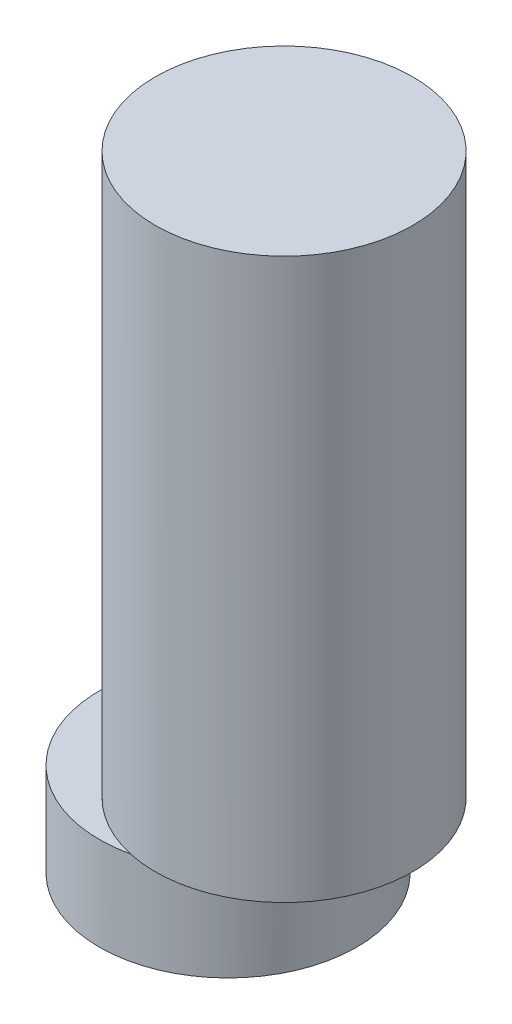
SolidWorks part; units mm, degrees
ref_plane "Front Plane" through (0, 0, 0) normal (0, 0, 1) x (1, 0, 0)
ref_plane "Top Plane" through (0, 0, 0) normal (0, 1, 0) x (1, 0, 0)
ref_plane "Right Plane" through (0, 0, 0) normal (1, 0, 0) x (0, 0, -1)
sketch "Sketch1" plane through (0, 0, 0) normal (0, 1, 0) x (1, 0, 0)
  circle A0 centre (0, 0) radius 3.45
  dimension "D1" = 6.9
extrude "Boss-Extrude1" add sketch "Sketch1" along normal blind 2.5
sketch "Sketch2" plane through (0, 2.5, 0) normal (0, 1, 0) x (1, 0, 0)
  line L0 (0, 0) -> (1.5, 0) construction
  circle A0 centre (1.5, 0) radius 3.45
  dimension "D2" = 6.9
  dimension "D1" = 1.5
extrude "Boss-Extrude2" add sketch "Sketch2" along normal blind 15
sketch "Sketch3" plane through (0, 0, 0) normal (0, -1, 0) x (1, 0, 0)
  arc A0 (0.75, -3.3675) -> (0.75, 3.3675) centre (1.5, 0) ccw construction
  arc A1 (0.75, 3.3675) -> (0.75, -3.3675) centre (1.5, 0) ccw construction
  arc A2 (0.75, -3.3675) -> (0.75, 3.3675) centre (1.5, 0) ccw
  arc A3 (0.75, 3.3675) -> (0.75, -3.3675) centre (1.5, 0) ccw
